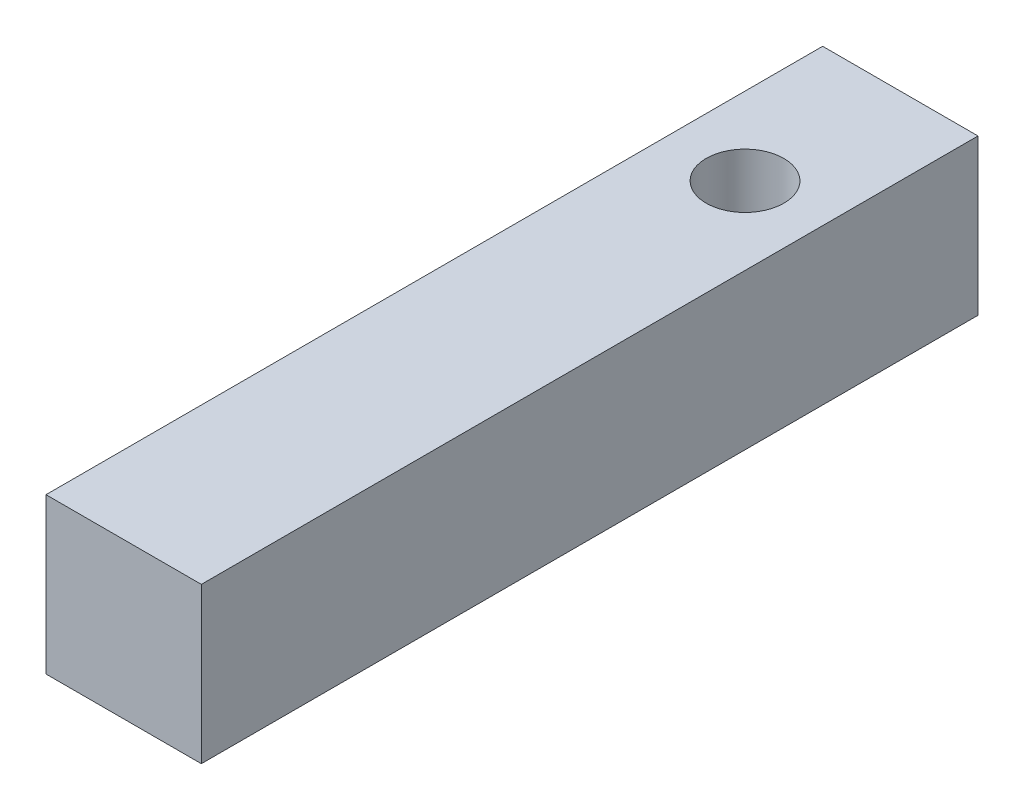
SolidWorks part; units mm, degrees
ref_plane "Front Plane" through (0, 0, 0) normal (0, 0, 1) x (1, 0, 0)
ref_plane "Top Plane" through (0, 0, 0) normal (0, 1, 0) x (1, 0, 0)
ref_plane "Right Plane" through (0, 0, 0) normal (1, 0, 0) x (0, 0, -1)
sketch "Sketch1" plane through (0, 0, 0) normal (0, 0, 1) x (1, 0, 0)
  line L1 (-15, -15) -> (15, -15)
  line L2 (-15, -15) -> (-15, 15)
  line L3 (-15, 15) -> (15, 15)
  line L4 (15, -15) -> (15, 15)
  line L5 (-15, -15) -> (15, 15) construction
  line L6 (-15, 15) -> (15, -15) construction
  point P0 (0, 0)
  dimension "D1" = 30
  dimension "D2" = 30
extrude "Boss-Extrude1" add sketch "Sketch1" along normal blind 150
sketch "Sketch2" plane through (0, -15, 0) normal (0, -1, 0) x (1, 0, 0)
  line L0 (0, 0) -> (0, 30) construction
  circle A0 centre (0, 30) radius 7.5
  dimension "D2" = 15
  dimension "D1" = 30
extrude "Cut-Extrude1" cut sketch "Sketch2" against normal blind 150
